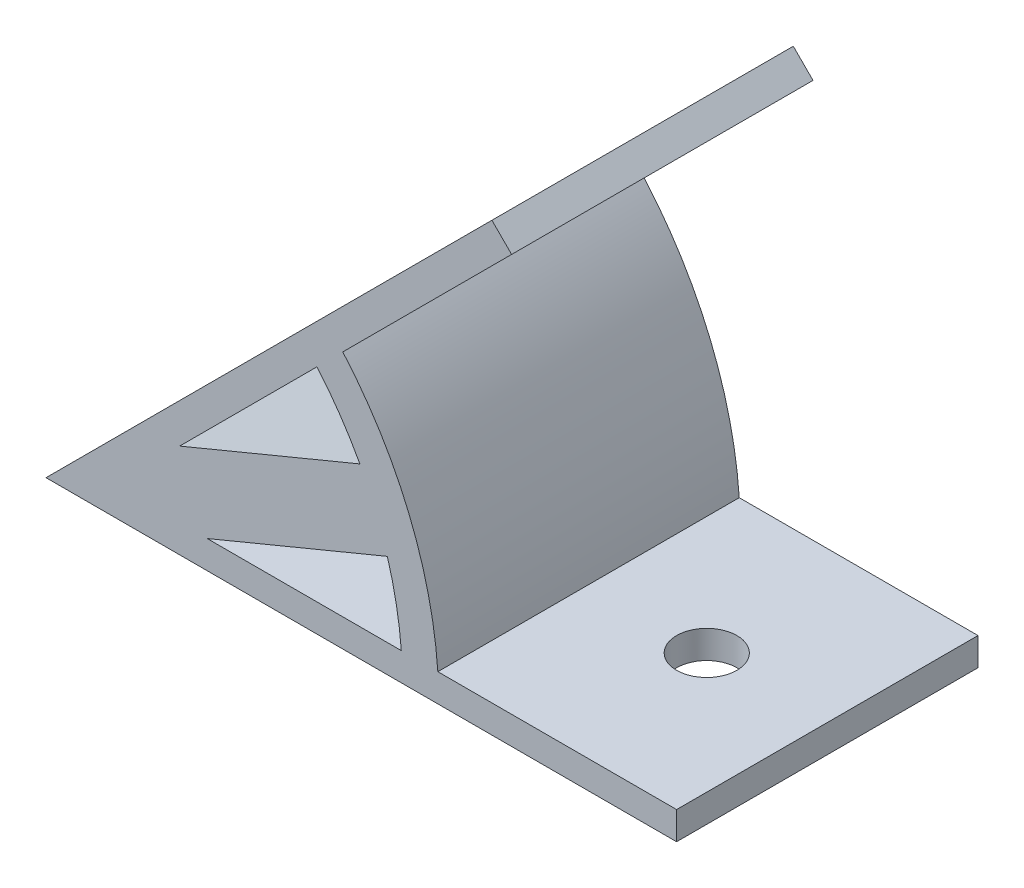
SolidWorks part; units mm, degrees
ref_plane "前基準面" through (0, 0, 0) normal (0, 0, 1) x (1, 0, 0)
ref_plane "上基準面" through (0, 0, 0) normal (0, 1, 0) x (1, 0, 0)
ref_plane "右基準面" through (0, 0, 0) normal (1, 0, 0) x (0, 0, -1)
sketch "草圖1" plane through (0, 0, 0) normal (0, 0, 1) x (1, 0, 0)
  line L0 (0, 0) -> (52.3056, 0) construction
  line L1 (0, 0) -> (52.3056, 21.6657) construction
  line L2 (0, 0) -> (52.3056, 0)
  line L7 (52.3056, 0) -> (52.3056, 2.3145)
  line L8 (52.3056, 2.3145) -> (32.5014, 2.3145)
  line L9 (29.471, 2.3145) -> (13.3687, 2.3145)
  line L10 (13.3687, 2.3145) -> (28.3121, 8.5043)
  line L11 (0, 0) -> (36.9856, 36.9856) construction
  line L12 (11.0897, 7.8165) -> (26.0331, 14.0062)
  line L13 (22.4757, 19.2025) -> (11.0897, 7.8165)
  line L14 (38.6222, 35.349) -> (24.6186, 21.3454)
  line L15 (36.9856, 36.9856) -> (38.6222, 35.349)
  line L16 (0, 0) -> (36.9856, 36.9856)
  arc A2 (32.5014, 2.3145) -> (24.6186, 21.3454) centre (0, 0) ccw
  arc A3 (29.471, 2.3145) -> (28.3121, 8.5043) centre (0, 0) ccw
  arc A4 (22.4757, 19.2025) -> (26.0331, 14.0062) centre (0, 0) cw
  dimension "D1" = 22.5
extrude "填料-伸長1" add sketch "草圖1" along normal blind 25
sketch "草圖4" plane through (0, 0, 0) normal (0, -1, 0) x (1, 0, 0)
  line L0 (0, 12.5) -> (52.3056, 12.5) construction
  line L1 (0, 25) -> (0, 0) construction
  line L2 (52.3056, 25) -> (52.3056, 0) construction
  circle A0 centre (42.3056, 12.5) radius 2.5
  dimension "D1" = 10
  dimension "D2" = 5
extrude "除料-伸長1" cut sketch "草圖4" against normal through all
sketch "草圖5" plane through (0, 0, 0) normal (-0.7071, 0.7071, 0) x (0, 0, 1)
  line L0 (12.5, 52.3056) -> (12.5, 0) construction
  line L1 (25, 52.3056) -> (0, 52.3056) construction
  line L2 (25, 0) -> (0, 0) construction
  circle A0 centre (12.5, 42.3056) radius 2.5
  dimension "D1" = 5
  dimension "D2" = 10
extrude "除料-伸長2" cut sketch "草圖5" against normal through all
